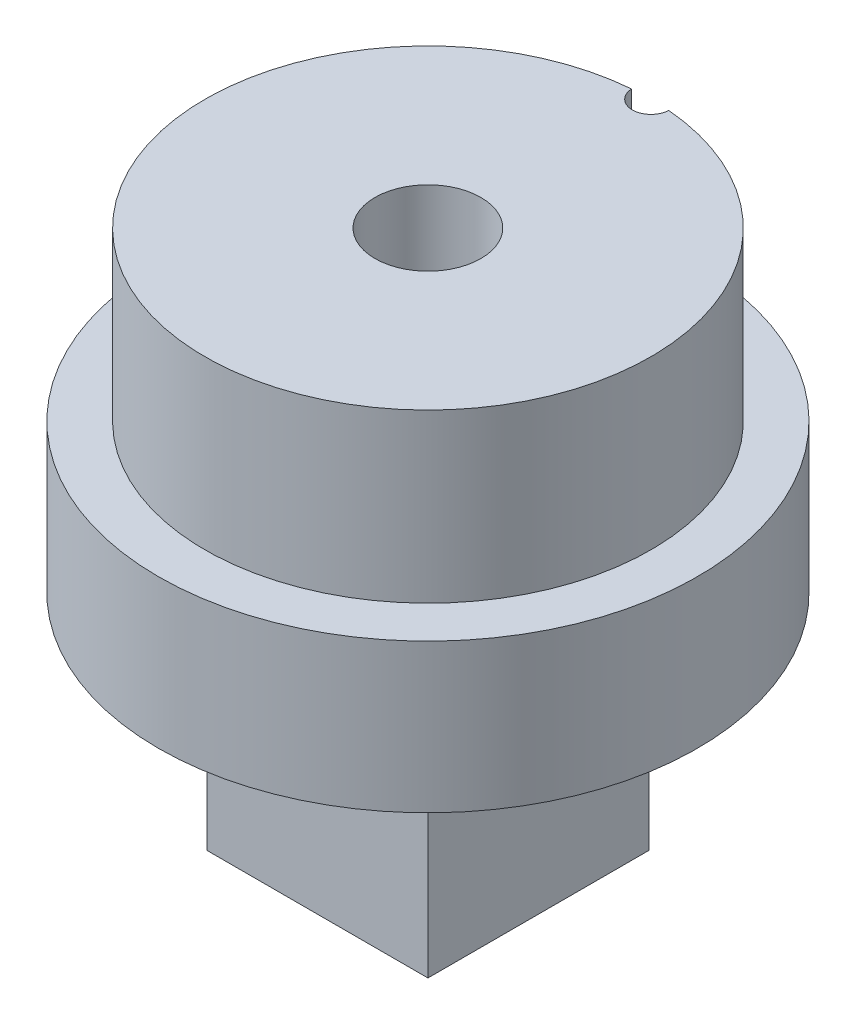
SolidWorks part; units mm, degrees
ref_plane "Front Plane" through (0, 0, 0) normal (0, 0, 1) x (1, 0, 0)
ref_plane "Top Plane" through (0, 0, 0) normal (0, 1, 0) x (1, 0, 0)
ref_plane "Right Plane" through (0, 0, 0) normal (1, 0, 0) x (0, 0, -1)
sketch "Sketch1" plane through (0, 0, 0) normal (0, 1, 0) x (1, 0, 0)
  line L1 (-2.975, -2.975) -> (2.975, -2.975)
  line L2 (-2.975, -2.975) -> (-2.975, 2.975)
  line L3 (-2.975, 2.975) -> (2.975, 2.975)
  line L4 (2.975, -2.975) -> (2.975, 2.975)
  line L5 (-2.975, -2.975) -> (2.975, 2.975) construction
  line L6 (-2.975, 2.975) -> (2.975, -2.975) construction
  point P0 (0, 0)
  dimension "D1" = 5.95
extrude "Boss-Extrude1" add sketch "Sketch1" along normal blind 6
sketch "Sketch2" plane through (0, 6, 0) normal (0, 1, 0) x (1, 0, 0)
  circle A0 centre (0, 0) radius 7.25
  dimension "D1" = 14.5
extrude "Boss-Extrude2" add sketch "Sketch2" along normal blind 4
sketch "Sketch3" plane through (0, 0, 0) normal (0, -1, 0) x (1, 0, 0)
  circle A0 centre (0, 0) radius 1.425
  dimension "D1" = 2.85
extrude "Cut-Extrude1" cut sketch "Sketch3" against normal through all
sketch "Sketch4" plane through (0, 10, 0) normal (0, 1, 0) x (1, 0, 0)
  circle A0 centre (0, 0) radius 6
  circle A1 centre (0, 6) radius 0.5
  dimension "D1" = 12
  dimension "D2" = 1
extrude "Boss-Extrude4" add sketch "Sketch4" along normal blind 4.5 contours A1 A0
